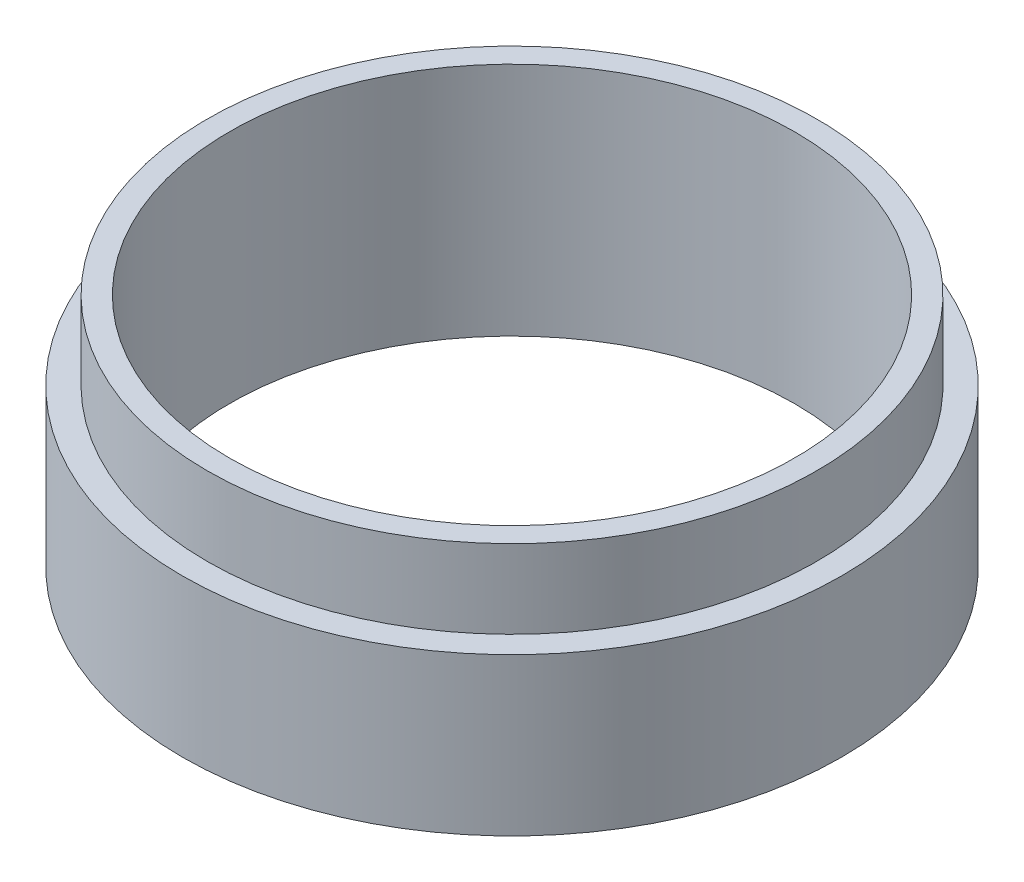
SolidWorks part; units mm, degrees
ref_plane "Front Plane" through (0, 0, 0) normal (0, 0, 1) x (1, 0, 0)
ref_plane "Top Plane" through (0, 0, 0) normal (0, 1, 0) x (1, 0, 0)
ref_plane "Right Plane" through (0, 0, 0) normal (1, 0, 0) x (0, 0, -1)
sketch "Sketch1" plane through (0, 0, 0) normal (0, 0, 1) x (1, 0, 0)
  line L0 (0, 0) -> (0, 23374.4256) construction
  line L1 (0, 0) -> (23374.4256, 0) construction
  line L3 (0, 10) -> (21, 10)
  line L4 (0, 10) -> (0, 0)
  line L5 (0, 0) -> (21, 0)
  line L6 (21, 10) -> (21, 0)
  line L7 (0, 10) -> (21, 0) construction
  line L8 (0, 0) -> (21, 10) construction
  point P5 (10.5, 5)
  dimension "D1" = 42
  dimension "D2" = 10
revolve "Revolve1" add sketch "Sketch1" angle 360 about L0
sketch "Sketch2" plane through (0, 10, 0) normal (0, 1, 0) x (1, 0, 0)
  circle A2 centre (0, 0) radius 18
  circle A3 centre (0, 0) radius 18
  dimension "D1" = 3
extrude "Cut-Extrude1" cut sketch "Sketch2" against normal through all
sketch "Sketch4" plane through (0, 10, 0) normal (0, 1, 0) x (1, 0, 0)
  circle A3 centre (0, 0) radius 19.41
  circle A4 centre (0, 0) radius 19.41
  dimension "D1" = 1.41
extrude "Boss-Extrude1" add sketch "Sketch4" along normal blind 5
sketch "Sketch5" plane through (0, 15, 0) normal (0, 1, 0) x (1, 0, 0)
  circle A2 centre (0, 0) radius 18
  circle A3 centre (0, 0) radius 18
  dimension "D1" = 3
extrude "Cut-Extrude2" cut sketch "Sketch5" against normal through all
